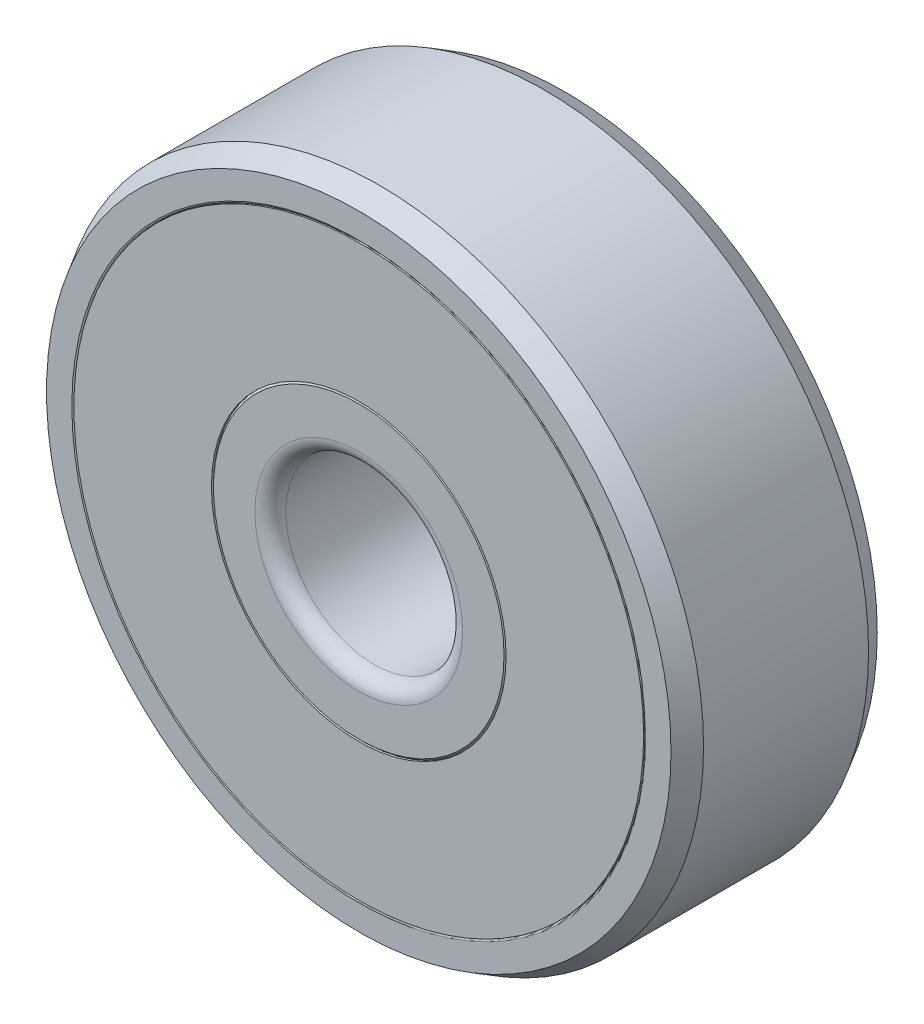
SolidWorks part; units mm, degrees
ref_plane "Front Plane" through (0, 0, 0) normal (0, 0, 1) x (1, 0, 0)
ref_plane "Top Plane" through (0, 0, 0) normal (0, 1, 0) x (1, 0, 0)
ref_plane "Right Plane" through (0, 0, 0) normal (1, 0, 0) x (0, 0, -1)
sketch "Sketch1" plane through (0, 0, 0) normal (0, 0, 1) x (1, 0, 0)
  line L0 (0, 7) -> (0, 11) construction
  line L1 (0, 3) -> (0, 7) construction
  line L2 (0, 11) -> (0, 9.6667) construction
  line L3 (0, 9.6667) -> (0, 8.3333) construction
  line L4 (0, 8.3333) -> (0, 7) construction
  circle A0 centre (0, 0) radius 3
  circle A1 centre (0, 0) radius 11
  circle A2 centre (0, 0) radius 9.6667 construction
  circle A4 centre (0, 0) radius 5 construction
  point P6 (0, 5)
  dimension "OD" = 22
  dimension "ID" = 6
sketch "Sketch2" plane through (0, 0, 0) normal (1, 0, 0) x (0, 0, -1)
  line L0 (-3.5, 11) -> (3.5, 11) construction
  line L1 (3.5, 11) -> (3.5, -11) construction
  line L2 (3.5, 0) -> (-3.5, 0) construction
  line L3 (-3.5, 3) -> (-3.5, -3) construction
  point P2 (0, 11)
  dimension "Width" = 7
  dimension "For Shaft Diameter" = 6
  dimension "For Housing ID" = 22
sketch "Sketch3" plane through (0, 0, 0) normal (1, 0, 0) x (0, 0, -1)
  line L0 (-2.8, -11) -> (2.8, -11)
  line L3 (-3.5, -9.7367) -> (-3.5, -10.5959)
  line L4 (0, -5) -> (0, -9.6667) construction
  line L5 (-2.8, -11) -> (-3.5, -10.5959)
  line L6 (-2.975, -3) -> (2.975, -3)
  line L7 (-2.2222, -9.6667) -> (-2.2222, -10.1111) construction
  line L8 (-3.43, -5) -> (-2.2222, -5)
  line L9 (-3.5, -5) -> (0, -5) construction
  line L11 (-3.5, -9.6667) -> (-3.5, -5) construction
  line L12 (-3.5, -4.93) -> (-3.5, -3.525)
  line L14 (-3.5, 0) -> (3.5, 0) construction
  line L15 (-3.43, -9.6667) -> (-2.2222, -9.6667)
  line L17 (0, 0) -> (0, -11) construction
  line L18 (-2.2222, -10.1111) -> (-2.2222, -10.5556) construction
  line L19 (2.8, -11) -> (3.5, -10.5959)
  line L20 (0, -9.6667) -> (-3.5, -9.6667) construction
  line L21 (-3.5, 3) -> (-3.5, -3) construction
  line L22 (-2.2222, -10.5556) -> (-2.2222, -11) construction
  line L30 (-3.5, -4.93) -> (-3.43, -5)
  line L31 (3.43, -5) -> (2.2222, -5)
  line L32 (3.5, -4.93) -> (3.43, -5)
  line L33 (3.5, -4.93) -> (3.5, -3.525)
  line L34 (3.43, -9.6667) -> (2.2222, -9.6667)
  line L35 (3.5, -9.7367) -> (3.5, -10.5959)
  line L36 (0, 11) -> (0, -11) construction
  arc A0 (0, -4.1111) -> (0, -10.5556) centre (0, -7.3333) ccw construction
  arc A1 (-2.2222, -5) -> (2.2222, -5) centre (0, -7.3333) cw
  arc A2 (-2.2222, -9.6667) -> (2.2222, -9.6667) centre (0, -7.3333) ccw
  arc A4 (-3.43, -9.6667) -> (-3.5, -9.7367) centre (-3.43, -9.7367) ccw
  arc A5 (-2.975, -3) -> (-3.5, -3.525) centre (-2.975, -3.525) ccw
  arc A6 (2.975, -3) -> (3.5, -3.525) centre (2.975, -3.525) cw
  arc A7 (3.43, -9.6667) -> (3.5, -9.7367) centre (3.43, -9.7367) cw
  point P28 (0, -7.3333)
  point P46 (-3.5, -3)
  point P54 (0, -3)
  dimension "D4" = 0.07
  dimension "D7" = 0.525
  dimension "D5" = 45
  dimension "D6" = 0.07
  dimension "D3" = 0.7
  dimension "D2" = 60
revolve "Revolve1" add sketch "Sketch3" angle 360 about L14
sketch "Sketch4" plane through (0, 0, 0) normal (1, 0, 0) x (0, 0, -1)
  line L0 (-3.43, -9.6667) -> (-2.2222, -9.6667) construction
  line L1 (-3.5, -5) -> (-3.2917, -5)
  line L2 (-3.5, -5) -> (-3.5, -9.6667)
  line L3 (-3.5, -9.6667) -> (-3.2917, -9.6667)
  line L4 (-3.2917, -5) -> (-3.2917, -9.6667)
  line L5 (-3.5, -4.93) -> (-3.5, -3.525) construction
  line L6 (-3.5, -7.3333) -> (-3.4306, -7.3333) construction
  line L7 (-3.4306, -7.3333) -> (-3.3611, -7.3333) construction
  line L8 (-3.3611, -7.3333) -> (-3.2917, -7.3333) construction
  line L9 (-3.2917, -7.3333) -> (-3.2222, -7.3333) construction
  line L10 (-3.5, -9.6667) -> (-3.5, -5) construction
  line L11 (-3.43, -5) -> (-2.2222, -5) construction
  arc A1 (0, -4.1111) -> (0, -10.5556) centre (0, -7.3333) ccw construction
revolve "Revolve2" add sketch "Sketch4" angle 360 about L14
sketch "Sketch5" plane through (0, 0, 0) normal (1, 0, 0) x (0, 0, -1)
  line L2 (0, -4.1111) -> (0, -10.5556)
  arc A2 (0, -10.5556) -> (0, -4.1111) centre (0, -7.3333) cw
revolve "Revolve3" add sketch "Sketch5" angle 360 about L17
pattern_circular "CirPattern1" count 7 over 360 about axis through (0, 0, 0) along (0, 0, 1) of bodies 138
equation "\"D4@Sketch3\"=\"Width@Sketch2\"*.01"
equation "\"D6@Sketch3\"=\"Width@Sketch2\"*.01"
equation "\"D7@Sketch3\"=\"Width@Sketch2\"*.075"
equation "\"D3@Sketch3\"=\"Width@Sketch2\"*.1"
